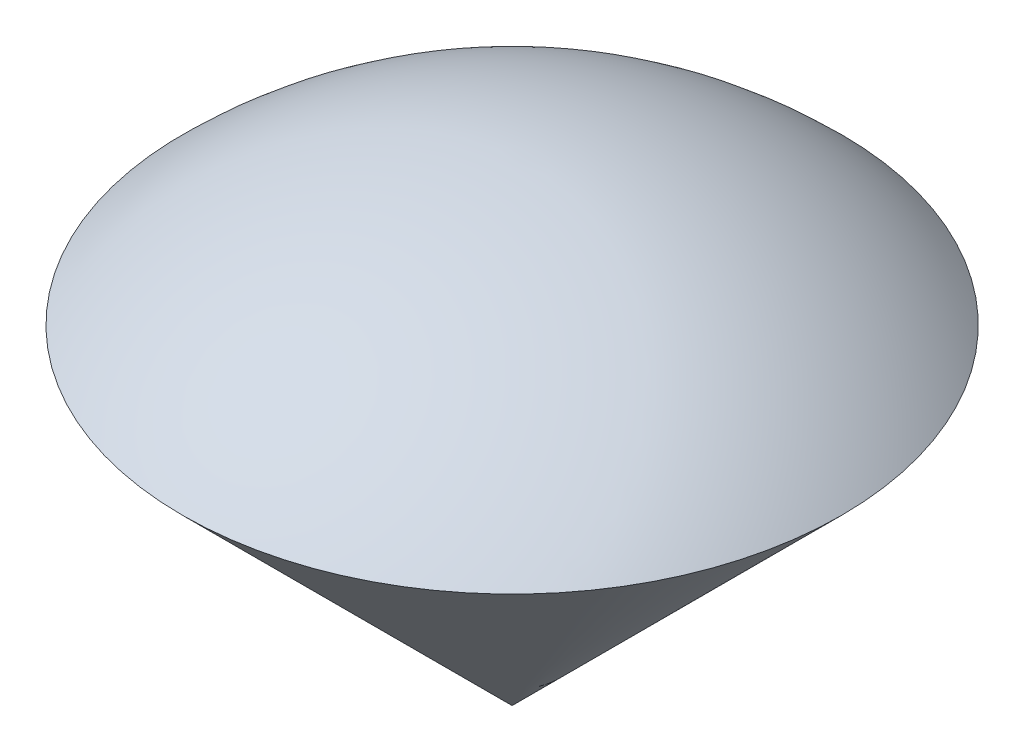
SolidWorks part; units mm, degrees
ref_plane "Front Plane" through (0, 0, 0) normal (0, 0, 1) x (1, 0, 0)
ref_plane "Top Plane" through (0, 0, 0) normal (0, 1, 0) x (1, 0, 0)
ref_plane "Right Plane" through (0, 0, 0) normal (1, 0, 0) x (0, 0, -1)
sketch "Sketch1" plane through (0, 0, 0) normal (0, 0, 1) x (1, 0, 0)
  line L0 (3.5355, 3.5355) -> (0, 0)
  line L2 (0, 0) -> (0, 5)
  arc A0 (3.5355, 3.5355) -> (0, 5) centre (0, 0) ccw
  dimension "D1" = 10
  dimension "D2" = 45
revolve "Revolve1" add sketch "Sketch1" angle 360 about L2
